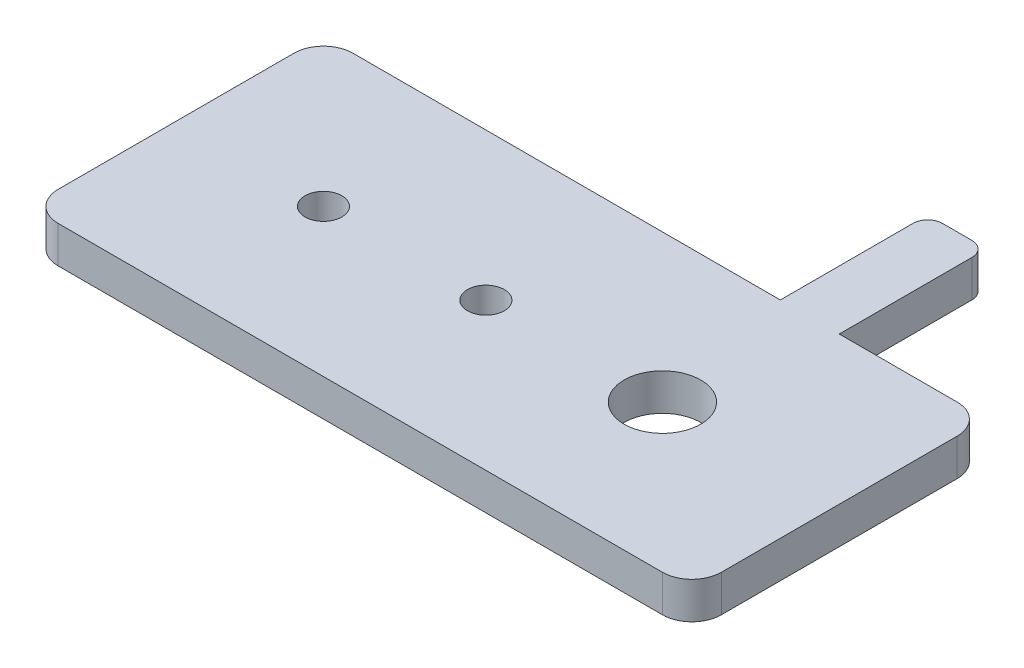
SolidWorks part; units mm, degrees
ref_plane "Front Plane" through (0, 0, 0) normal (0, 0, 1) x (1, 0, 0)
ref_plane "Top Plane" through (0, 0, 0) normal (0, 1, 0) x (1, 0, 0)
ref_plane "Right Plane" through (0, 0, 0) normal (1, 0, 0) x (0, 0, -1)
sketch "Sketch1" plane through (0, 0, 0) normal (0, 1, 0) x (1, 0, 0)
  line L0 (44.45, 25.4) -> (54.61, 25.4)
  line L1 (2.54, 0) -> (54.61, 0)
  line L2 (0, 2.54) -> (0, 22.86)
  line L3 (2.54, 25.4) -> (39.37, 25.4)
  line L4 (57.15, 2.54) -> (57.15, 22.86)
  line L6 (39.37, 25.4) -> (39.37, 36.83)
  line L7 (40.64, 38.1) -> (43.18, 38.1)
  line L8 (44.45, 25.4) -> (44.45, 36.83)
  arc A0 (54.61, 0) -> (57.15, 2.54) centre (54.61, 2.54) ccw
  arc A1 (54.61, 25.4) -> (57.15, 22.86) centre (54.61, 22.86) cw
  arc A2 (2.54, 0) -> (0, 2.54) centre (2.54, 2.54) cw
  arc A3 (0, 22.86) -> (2.54, 25.4) centre (2.54, 22.86) cw
  arc A4 (43.18, 38.1) -> (44.45, 36.83) centre (43.18, 36.83) cw
  arc A5 (39.37, 36.83) -> (40.64, 38.1) centre (40.64, 36.83) cw
  point P9 (57.15, 25.4)
  point P12 (0, 0)
  point P15 (0, 25.4)
  point P22 (44.45, 38.1)
  point P25 (39.37, 38.1)
  dimension "D3" = 2.54
  dimension "D7" = 1.27
  dimension "D1" = 25.4
  dimension "D2" = 57.15
  dimension "D4" = 12.7
  dimension "D5" = 5.08
  dimension "D6" = 12.7
extrude "Boss-Extrude1" add sketch "Sketch1" along normal blind 3.175
sketch "Sketch2" plane through (0, 3.175, 0) normal (0, 1, 0) x (1, 0, 0)
  line L0 (0, 12.7) -> (50000, 12.7) construction
  line L1 (0, 22.86) -> (0, 2.54) construction
  line L2 (57.15, 2.54) -> (57.15, 22.86) construction
  line L3 (44.45, 25.4) -> (44.45, 36.83) construction
  circle A0 centre (12.7, 12.7) radius 1.5875
  circle A1 centre (26.7, 12.7) radius 1.5875
  circle A2 centre (41.91, 12.7) radius 3.302
  point P4 (0, 12.7)
  point P7 (57.15, 12.7)
  dimension "D1" = 3.175
  dimension "D2" = 6.604
  dimension "D3" = 2.54
  dimension "D4" = 12.7
  dimension "D5" = 14
extrude "Cut-Extrude1" cut sketch "Sketch2" against normal up to next
